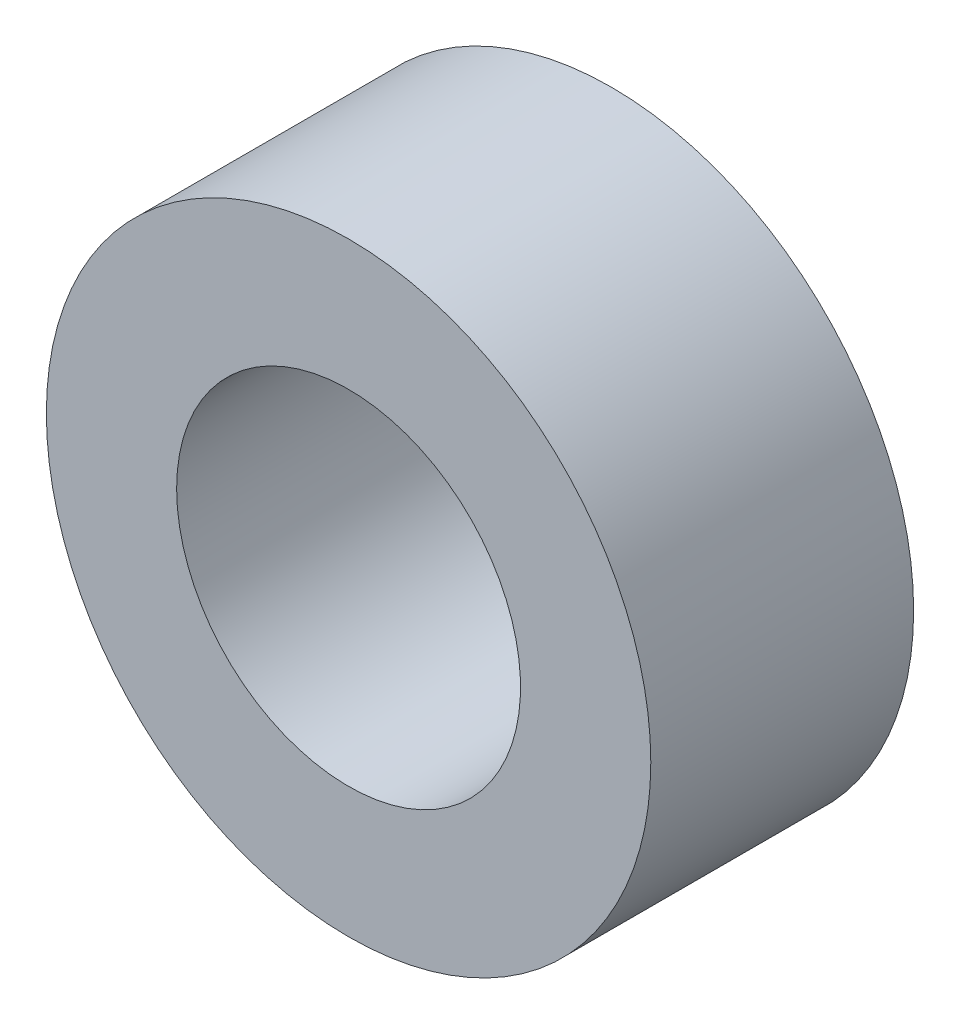
SolidWorks part; units mm, degrees
material "PET"
ref_plane "Front Plane" through (0, 0, 0) normal (0, 0, 1) x (1, 0, 0)
ref_plane "Top Plane" through (0, 0, 0) normal (0, 1, 0) x (1, 0, 0)
ref_plane "Right Plane" through (0, 0, 0) normal (1, 0, 0) x (0, 0, -1)
sketch "Sketch1" plane through (0, 0, 0) normal (0, 0, 1) x (1, 0, 0)
  circle A0 centre (0, 0) radius 4.191
  circle A1 centre (0, 0) radius 7.366
  dimension "D1" = 8.382
  dimension "D2" = 14.732
extrude "Boss-Extrude1" add sketch "Sketch1" along normal blind 6.4062
